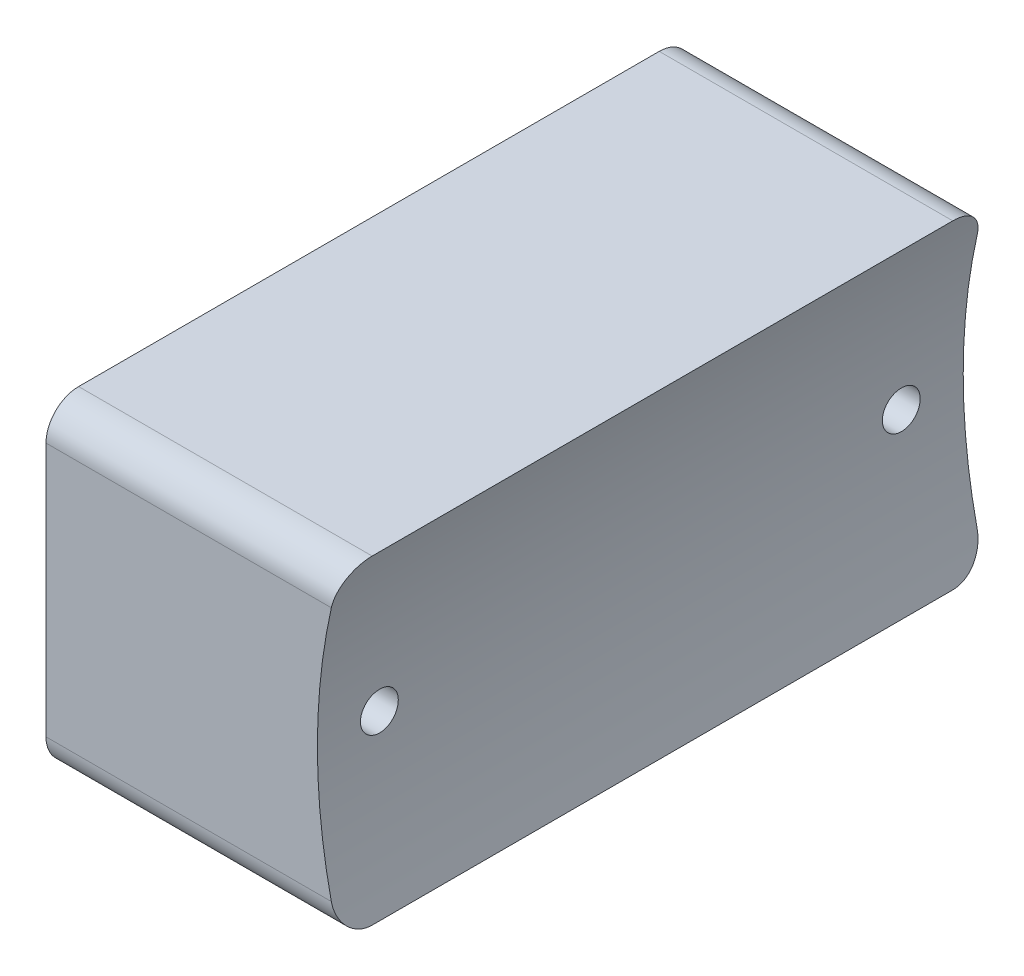
SolidWorks part; units mm, degrees
ref_plane "Спереди" through (0, 0, 0) normal (0, 0, 1) x (1, 0, 0)
ref_plane "Сверху" through (0, 0, 0) normal (0, 1, 0) x (1, 0, 0)
ref_plane "Справа" through (0, 0, 0) normal (1, 0, 0) x (0, 0, -1)
sketch "Эскиз1" plane through (0, 0, 0) normal (1, 0, 0) x (0, 0, -1)
  line L0 (-1050, 0) -> (48950, 0) construction
  line L1 (0, -1021.7777) -> (0, 48978.2223) construction
  line L2 (-24.75, -12.25) -> (24.75, -12.25)
  line L3 (-24.75, -12.25) -> (-24.75, 12.25)
  line L4 (-24.75, 12.25) -> (24.75, 12.25)
  line L5 (24.75, -12.25) -> (24.75, 12.25)
  line L6 (-24.75, -12.25) -> (24.75, 12.25) construction
  line L7 (-24.75, 12.25) -> (24.75, -12.25) construction
  point P3 (0, 0)
  dimension "D1" = 24.5
  dimension "D2" = 49.5
extrude "Бобышка-Вытянуть1" add sketch "Эскиз1" along normal blind 22.5
sketch "Эскиз2" plane through (0, 0, 0) normal (-1, 0, 0) x (0, 0, 1)
  line L1 (-24.75, -12.25) -> (-24.75, 12.25) construction
  line L2 (24.75, 12.25) -> (24.75, -12.25) construction
  line L3 (24.75, -12.25) -> (-24.75, -12.25) construction
  circle A0 centre (-20, -7.25) radius 2.5
  circle A1 centre (20, -7.25) radius 2.5
  dimension "D3" = 5
  dimension "D1" = 5
  dimension "D2" = 4.75
  dimension "D4" = 4.75
  dimension "D5" = 5
extrude "Вырез-Вытянуть1" cut sketch "Эскиз2" against normal blind 3
sketch "Эскиз3" plane through (0, 0, 0) normal (-1, 0, 0) x (0, 0, 1)
  line L0 (0, -1000) -> (0, 49000) construction
  line L1 (-7.6, 3.5) -> (7.6, 3.5)
  line L2 (-7.6, 7.5) -> (7.6, 7.5)
  line L3 (-7.6, 7.5) -> (-7.6, 10)
  line L4 (-7.6, 10) -> (7.6, 10)
  line L5 (7.6, 7.5) -> (7.6, 10)
  line L6 (-7.6, 7.5) -> (7.6, 10) construction
  line L7 (-7.6, 10) -> (7.6, 7.5) construction
  line L8 (-24.75, 12.25) -> (24.75, 12.25) construction
  line L9 (-7.6, 3.5) -> (-7.6, 6)
  line L10 (-7.6, 6) -> (7.6, 6)
  line L11 (7.6, 3.5) -> (7.6, 6)
  line L12 (-7.6, 3.5) -> (7.6, 6) construction
  line L13 (-7.6, 6) -> (7.6, 3.5) construction
  point P1 (0, 8.75)
  point P10 (0, 4.75)
  point P15 (0, 0)
  dimension "D1" = 15.2
  dimension "D2" = 2.5
  dimension "D3" = 2.25
  dimension "D4" = 15.2
  dimension "D5" = 2.5
  dimension "D6" = 4
extrude "Вырез-Вытянуть2" cut sketch "Эскиз3" against normal blind 8
sketch "Эскиз4" plane through (0, 0, -24.75) normal (0, 0, -1) x (-1, 0, 0)
  line L2 (-22.5, 12.25) -> (-22.5, -12.25)
  arc A0 (-38.4051, 35.7) -> (-38.4051, -35.7) centre (-65.8005, 0) cw construction
  arc A1 (-22.5, 12.25) -> (-22.5, -12.25) centre (-65.8005, 0) cw
  dimension "D1" = 71.4
  dimension "D2" = 45
extrude "Вырез-Вытянуть3" cut sketch "Эскиз4" against normal blind 50
sketch "Эскиз5" plane through (0, 0, 0) normal (1, 0, 0) x (0, 0, -1)
  line L0 (-1000, 0) -> (49000, 0) construction
  circle A0 centre (-20, 0) radius 1.45
  circle A1 centre (20, 0) radius 1.45
  dimension "D1" = 2.9
  dimension "D2" = 20
  dimension "D3" = 20
extrude "Вырез-Вытянуть4" cut sketch "Эскиз5" against normal blind 10 from offset 22.5
fillet "Скругление1" radius 2.5 4 edges at (11.25, -12.25, 24.75) (11.25, 12.25, 24.75) (11.25, -12.25, -24.75) (11.25, 12.25, -24.75)
